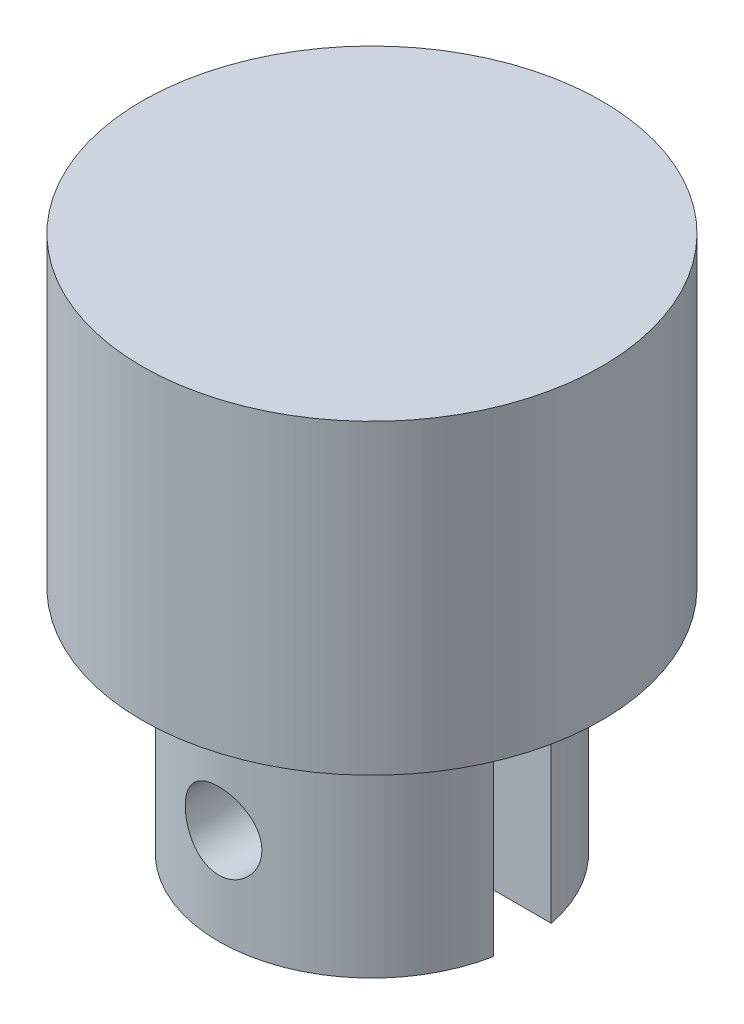
SolidWorks part; units mm, degrees
material "Tin Bearing Bronze"
ref_plane "Front Plane" through (0, 0, 0) normal (0, 0, 1) x (1, 0, 0)
ref_plane "Top Plane" through (0, 0, 0) normal (0, 1, 0) x (1, 0, 0)
ref_plane "Right Plane" through (0, 0, 0) normal (1, 0, 0) x (0, 0, -1)
sketch "Sketch1" plane through (0, 0, 0) normal (0, 1, 0) x (1, 0, 0)
  circle A0 centre (0, 0) radius 6
  dimension "D1" = 12
extrude "Boss-Extrude1" add sketch "Sketch1" along normal mid plane 8
sketch "Sketch2" plane through (0, -4, 0) normal (0, -1, 0) x (1, 0, 0)
  circle A0 centre (0, 0) radius 4
  dimension "D1" = 8
extrude "Boss-Extrude2" add sketch "Sketch2" along normal blind 6
hole_wizard "Ø2.0mm Press Dowel Hole1" positions "3DSketch1" profile "Sketch5" hole size "Ø2.0" standard "ISO"
sketch3d "3DSketch1"
  point P0 (0, -7.5, 4)
  point P3 (0, -7.5, -4)
  dimension "D1" = 2.5
  dimension "D2" = 2.5
sketch "Sketch5" plane through (0, -7.5, 4) normal (1, 0, 0) x (0, -1, 0)
  line L0 (0, 0) -> (0, 3.8509)
  line L1 (0, 3.8509) -> (1, 3.25)
  line L2 (1, 3.25) -> (1, 0)
  line L5 (1, 0) -> (0, 0)
  line L10 (0, 3.8509) -> (-1, 3.25) construction
  line L11 (0, -6.35) -> (0, 107.95) construction
  dimension "Hole Dia." = 2
  dimension "Hole Depth" = 3.25
  dimension "Drill Angle" = 118
sketch "Sketch8" plane through (0, 0, 0) normal (1, 0, 0) x (0, 0, -1)
  line L0 (-4, -10) -> (4, -10) construction
  line L1 (-0.75, -4) -> (0.75, -4)
  line L2 (-0.75, -4) -> (-0.75, -10)
  line L3 (-0.75, -10) -> (0.75, -10)
  line L4 (0.75, -4) -> (0.75, -10)
  line L5 (-0.75, -4) -> (0.75, -10) construction
  line L6 (-0.75, -10) -> (0.75, -4) construction
  line L7 (0, 0) -> (0, -10.891)
  point P0 (0, -7)
  dimension "D1" = 1.5
  dimension "D2" = 0.75
  dimension "D3" = 6
extrude "Cut-Extrude1" cut sketch "Sketch8" along normal through all both and the other way through all contours L1 L4 L3 L2
